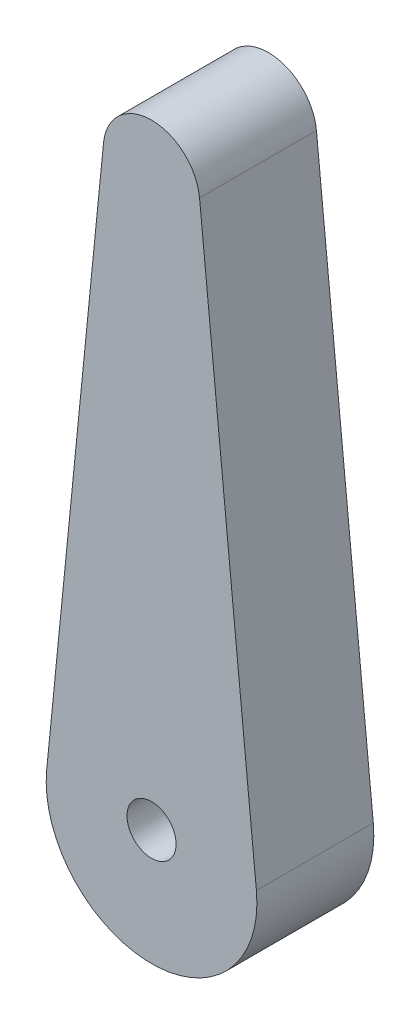
SolidWorks part; units mm, degrees
ref_plane "Front Plane" through (0, 0, 0) normal (1, 0, 0) x (0, 1, 0)
ref_plane "Top Plane" through (0, 0, 0) normal (0, 0, 1) x (0, 1, 0)
ref_plane "Right Plane" through (0, 0, 0) normal (0, 1, 0) x (-1, 0, 0)
sketch "Sketch1" plane through (0, 0, 0) normal (0, 0, 1) x (0, 1, 0)
  line L0 (0, 17.9375) -> (97.7538, 8.2119)
  line L1 (97.7538, -8.2119) -> (0, -17.9375)
  arc A2 (97.7538, 8.2119) -> (97.7538, -8.2119) centre (96.9368, 0) cw
  arc A3 (0, 17.9375) -> (0, -17.9375) centre (-1.7846, 0) ccw
  point P0 (-19.8107, 0)
  dimension "D1" = 125
extrude "Boss-Extrude1" add sketch "Sketch1" along normal blind 20
sketch "Sketch2" plane through (0, 0, 20) normal (0, 0, 1) x (1, 0, 0)
  circle A0 centre (0, 0) radius 4.2
  dimension "D1" = 8.4
extrude "Cut-Extrude1" cut sketch "Sketch2" against normal blind 17.5
